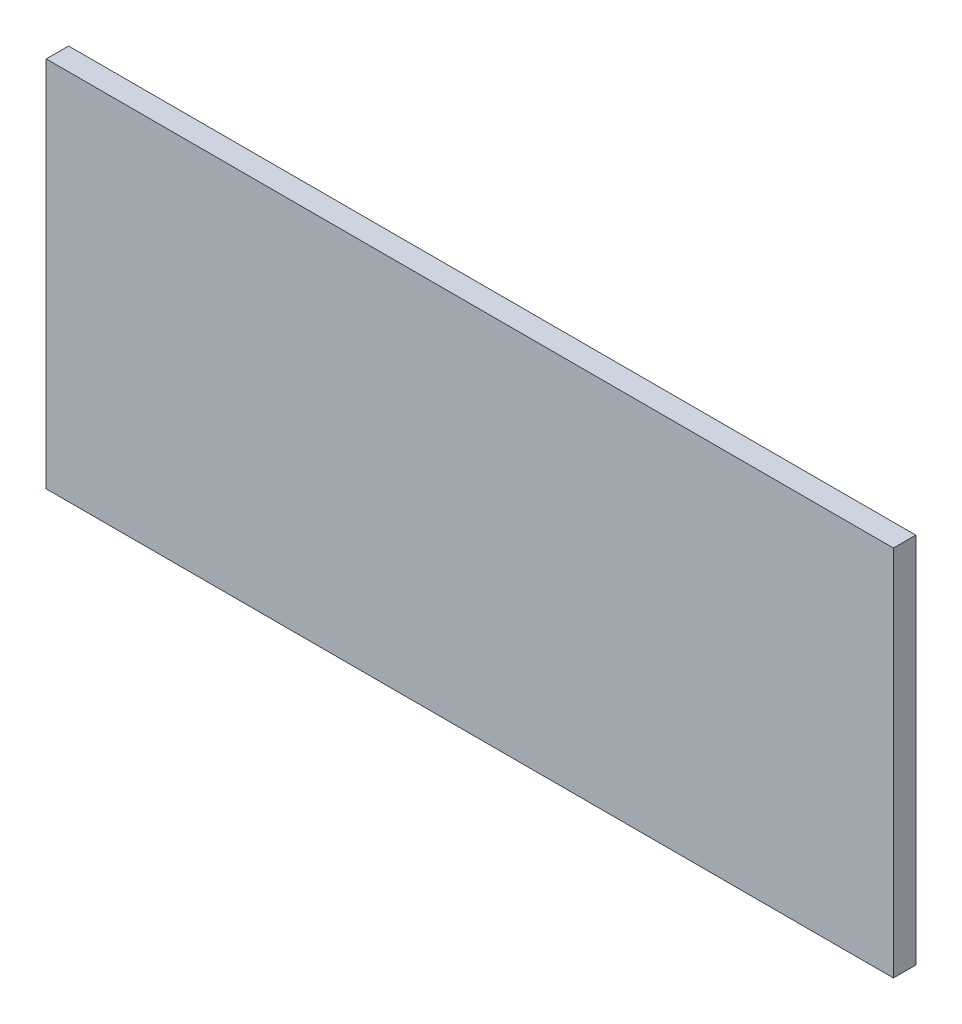
SolidWorks part; units mm, degrees
ref_plane "前视基准面" through (0, 0, 0) normal (0, 0, 1) x (1, 0, 0)
ref_plane "上视基准面" through (0, 0, 0) normal (0, 1, 0) x (1, 0, 0)
ref_plane "右视基准面" through (0, 0, 0) normal (1, 0, 0) x (0, 0, -1)
sketch "草图1" plane through (0, 0, 0) normal (0, 0, 1) x (1, 0, 0)
  line L1 (0, 0) -> (455, 0)
  line L2 (0, 0) -> (0, 200)
  line L3 (0, 200) -> (455, 200)
  line L4 (455, 0) -> (455, 200)
  dimension "D1" = 455
  dimension "D2" = 200
extrude "拉伸1" add sketch "草图1" along normal blind 12
